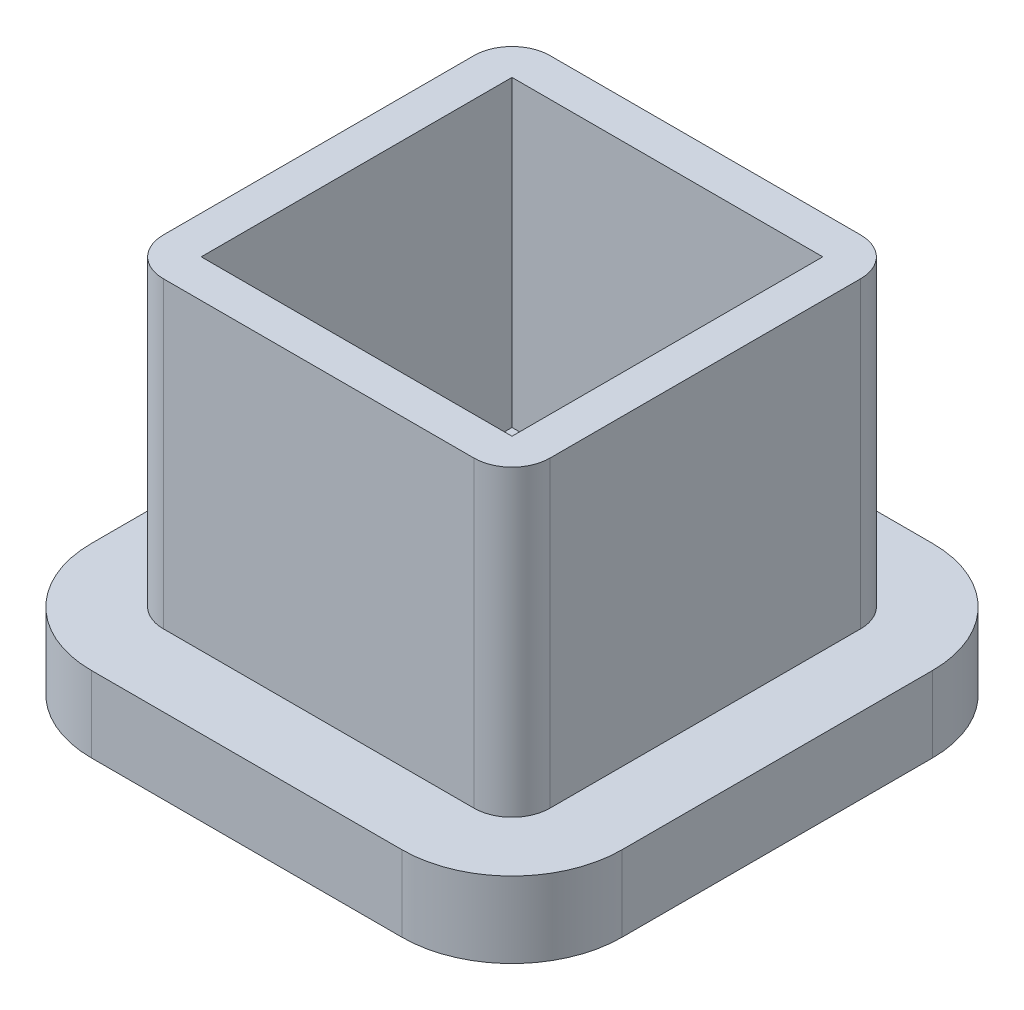
SolidWorks part; units mm, degrees
ref_plane "Front Plane" through (0, 0, 0) normal (0, 0, 1) x (1, 0, 0)
ref_plane "Top Plane" through (0, 0, 0) normal (0, 1, 0) x (1, 0, 0)
ref_plane "Right Plane" through (0, 0, 0) normal (1, 0, 0) x (0, 0, -1)
sketch "Sketch1" plane through (0, 0, 0) normal (0, 1, 0) x (1, 0, 0)
  line L1 (6.8067, -24.5146) -> (-28.1933, -24.5146)
  line L2 (6.8067, -24.5146) -> (6.8067, 10.4854)
  line L3 (6.8067, 10.4854) -> (-28.1933, 10.4854)
  line L4 (-28.1933, -24.5146) -> (-28.1933, 10.4854)
  dimension "D1" = 35
  dimension "D2" = 35
extrude "Boss-Extrude1" add sketch "Sketch1" along normal blind 5
sketch "Sketch2" plane through (0, 5, 0) normal (0, 1, 0) x (1, 0, 0)
  line L0 (6.8067, 10.4854) -> (-28.1933, 10.4854) construction
  line L1 (-20.9433, 3.2354) -> (-0.4433, 3.2354)
  line L2 (-20.9433, 3.2354) -> (-20.9433, -17.2646)
  line L3 (-20.9433, -17.2646) -> (-0.4433, -17.2646)
  line L4 (-0.4433, 3.2354) -> (-0.4433, -17.2646)
  line L5 (-28.1933, -24.5146) -> (6.8067, -24.5146) construction
  line L6 (-28.1933, 10.4854) -> (-28.1933, -24.5146) construction
  line L7 (6.8067, -24.5146) -> (6.8067, 10.4854) construction
  line L9 (-23.4433, 5.7354) -> (2.0567, 5.7354)
  line L10 (-23.4433, 5.7354) -> (-23.4433, -19.7646)
  line L11 (-23.4433, -19.7646) -> (2.0567, -19.7646)
  line L12 (2.0567, 5.7354) -> (2.0567, -19.7646)
  dimension "D1" = 7.25
  dimension "D2" = 7.25
  dimension "D3" = 7.25
  dimension "D4" = 7.25
  dimension "D5" = 2.5
  dimension "D6" = 2.5
  dimension "D7" = 2.5
  dimension "D8" = 2.5
extrude "Boss-Extrude2" add sketch "Sketch2" along normal blind 20
fillet "Fillet1" radius 7.25 4 edges at (-28.1933, 2.5, 24.5146) (-28.1933, 2.5, -10.4854) (6.8067, 2.5, 24.5146) (6.8067, 2.5, -10.4854)
fillet "Fillet2" radius 2.5 4 edges at (-23.4433, 15, 19.7646) (2.0567, 15, 19.7646) (2.0567, 15, -5.7354) (-23.4433, 15, -5.7354)
